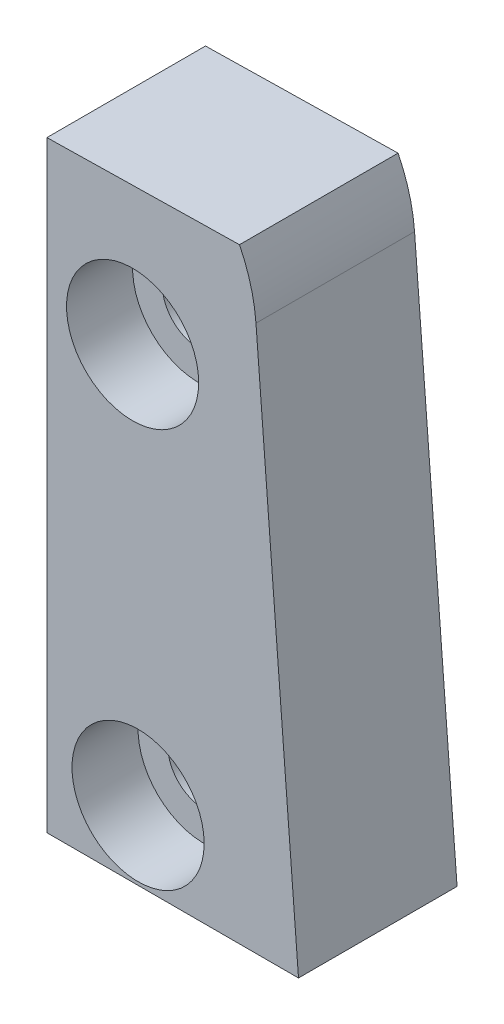
SolidWorks part; units mm, degrees
ref_plane "Front Plane" through (0, 0, 0) normal (1, 0, 0) x (0, 1, 0)
ref_plane "Top Plane" through (0, 0, 0) normal (0, 0, 1) x (0, 1, 0)
ref_plane "Right Plane" through (0, 0, 0) normal (0, 1, 0) x (-1, 0, 0)
sketch "Sketch1" plane through (0, 0, 0) normal (0, 0, 1) x (0, 1, 0)
  line L0 (6.83, -2.3448) -> (-9.6907, -3.6318)
  line L1 (7.2691, 3.9596) -> (8.5318, 3.9826)
  line L2 (-9.6907, -3.6318) -> (-9.6907, -2.2054)
  line L3 (8.5318, 3.9826) -> (8.6382, -1.8458)
  line L4 (-9.6907, 3.1951) -> (6.8764, 3.4236) construction
  line L5 (6.8764, 3.4236) -> (6.9454, -1.5759) construction
  line L6 (6.9454, -1.5759) -> (-9.6907, -1.8054) construction
  line L7 (-9.6907, -2.2054) -> (6.9475, -1.9759)
  line L8 (6.9475, -1.9759) -> (7.3509, -1.9703)
  line L9 (7.3509, -1.9703) -> (7.2691, 3.9596)
  arc A0 (6.83, -2.3448) -> (8.6382, -1.8458) centre (6.4473, 2.5673) ccw
  circle A1 centre (-7.5946, 1.2238) radius 1.1 construction
  circle A2 centre (4.4042, 1.3893) radius 1.1 construction
  point P0 (-0.6778, 0.862)
  dimension "D1" = 2.2
  dimension "D5" = 4.927
  dimension "D8" = 2.2
  dimension "D4" = 5.8284
  dimension "D6" = 16.5207
  dimension "D7" = 1.287
  dimension "D9" = 12
  dimension "D10" = 5.5287
  dimension "D12" = 0.4
  dimension "D13" = 0.4
  dimension "D14" = 0.4
extrude "Boss-Extrude1" add sketch "Sketch1" along normal blind 1.8
sketch "Sketch3" plane through (0, 0, 1.8) normal (0, 0, 1) x (1, 0, 0)
  line L0 (-3.9826, 8.5318) -> (-3.9826, -9.6907)
  line L1 (-3.9826, -9.6907) -> (3.6318, -9.6907)
  line L2 (3.6318, -9.6907) -> (2.3448, 6.83)
  line L3 (-3.9826, 8.5318) -> (1.8458, 8.6382)
  circle A0 centre (-1.2238, -7.5946) radius 1.1
  circle A1 centre (-1.3893, 4.4042) radius 1.1
  arc A3 (2.3448, 6.83) -> (1.8458, 8.6382) centre (-2.5673, 6.4473) ccw
extrude "Boss-Extrude2" add sketch "Sketch3" along normal blind 3
sketch "Sketch4" plane through (0, 0, 1.8) normal (0, 0, -1) x (1, 0, 0)
  line L0 (-3.9826, -8.5318) -> (-3.9826, 9.6907) construction
  line L1 (0.5464, 5.1999) -> (0.5464, -1.9847)
  line L2 (0.5464, 5.1999) -> (-2.9536, 5.1999)
  line L3 (-2.9536, 5.1999) -> (-2.9536, -1.9847)
  line L4 (0.5464, -1.9847) -> (-2.9536, -1.9847)
  line L5 (0.5464, 5.1999) -> (-2.9536, -1.9847) construction
  line L6 (-2.9536, 5.1999) -> (0.5464, -1.9847) construction
  line L7 (-3.9826, 9.6907) -> (2.2054, 9.6907) construction
  point P2 (-1.2036, 1.6076)
  point P9 (0.5464, -1.9847)
  dimension "D1" = 1.0291
  dimension "D2" = 4.4908
  dimension "D3" = 3.5
extrude "Cut-Extrude1" cut sketch "Sketch4" against normal blind 2
sketch "Sketch5" plane through (0, 0, 4.8) normal (0, 0, 1) x (1, 0, 0)
  circle A0 centre (-1.3893, 4.4042) radius 2
  circle A1 centre (-1.2238, -7.5946) radius 2
  dimension "D1" = 4
  dimension "D2" = 4
extrude "Cut-Extrude2" cut sketch "Sketch5" against normal blind 2
